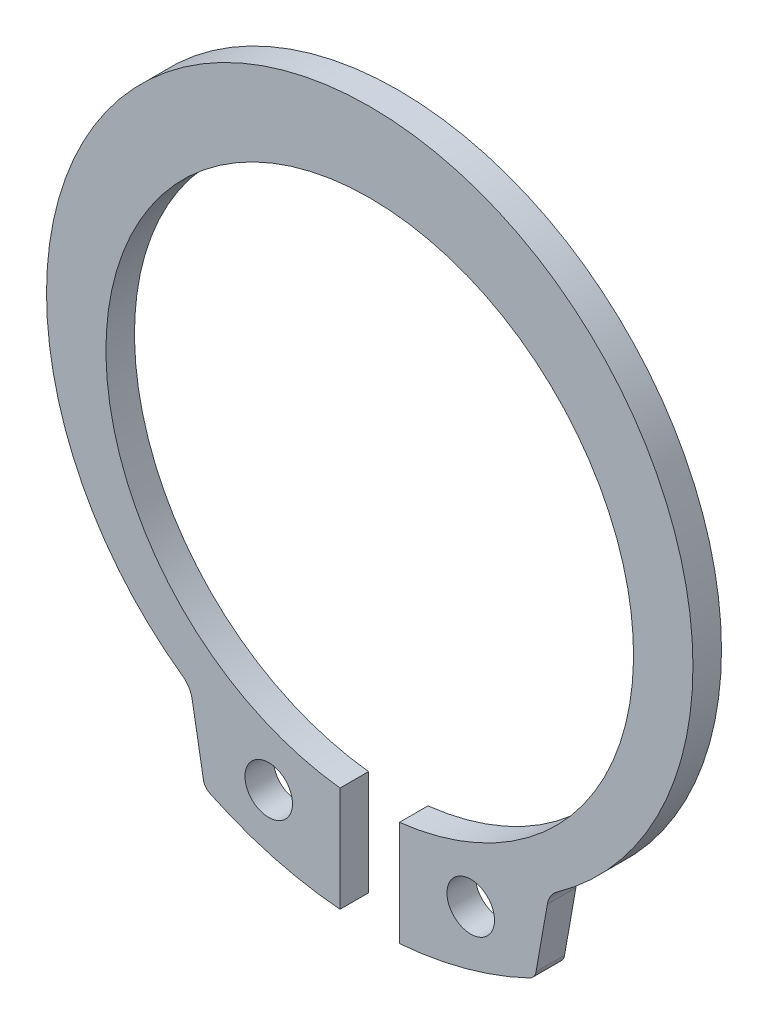
SolidWorks part; units mm, degrees
ref_plane "Front" through (0, 0, 0) normal (0, 0, 1) x (1, 0, 0)
ref_plane "Top" through (0, 0, 0) normal (0, 1, 0) x (1, 0, 0)
ref_plane "Right" through (0, 0, 0) normal (1, 0, 0) x (0, 0, -1)
sketch "Sketch1" plane through (0, 0, 0) normal (0, 0, 1) x (1, 0, 0)
  line L0 (0, 4.2365) -> (0, -4.9012) construction
  line L1 (-1.25, -11.8594) -> (-1.25, -16.2795)
  line L2 (1.25, -11.8594) -> (1.25, -16.2795)
  line L3 (13.3, -0.83) -> (-13.3, -0.83) construction
  line L4 (7.547, -11.3138) -> (6.953, -14.683)
  line L7 (-7.547, -11.3138) -> (-6.953, -14.683)
  line L8 (-7.547, -11.3138) -> (-7.547, -19.3845) construction
  arc A0 (1.25, -11.8594) -> (-1.25, -11.8594) centre (0, -0.83) ccw
  arc A1 (7.547, -11.3138) -> (-7.547, -11.3138) centre (0, 0) ccw
  arc A2 (-13.3, -0.83) -> (13.3, -0.83) centre (0, -0.83) ccw construction
  arc A3 (6.953, -14.683) -> (1.25, -16.2795) centre (0, -0.83) cw
  arc A4 (-6.953, -14.683) -> (-1.25, -16.2795) centre (0, -0.83) ccw
  circle A5 centre (4.25, -13.4327) radius 1
  circle A6 centre (-4.25, -13.4327) radius 1
  point P17 (-7.25, -12.9984)
  dimension "d" = 22.2
  dimension "D2" = 10
  dimension "d0" = 27.2
  dimension "d1" = 2
  dimension "R1" = 13.3
  dimension "R" = 15.5
  dimension "B1" = 2.5
  dimension "C" = 0.83
  dimension "L" = 14.5
  dimension "B2" = 8.5
extrude "Body" add sketch "Sketch1" against normal blind 1.2
fillet "Fillet1" radius 0.5 2 edges at (-6.953, -14.683, -0.6) (6.953, -14.683, -0.6)
fillet "Fillet2" radius 1 2 edges at (7.547, -11.3138, -0.6) (-7.547, -11.3138, -0.6)
scale "缩放比例1" scale about origin uniform scaling yes scale factor 0.25
